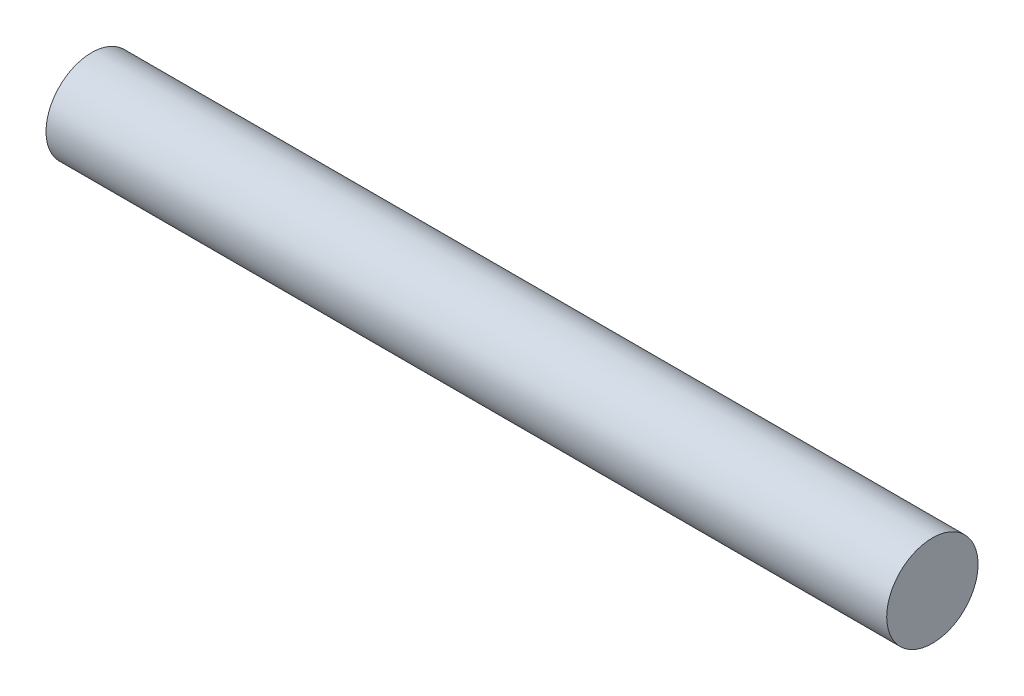
SolidWorks part; units mm, degrees
material "镀铬光轴"
ref_plane "前视" through (0, 0, 0) normal (0, 0, 1) x (1, 0, 0)
ref_plane "上视" through (0, 0, 0) normal (0, 1, 0) x (1, 0, 0)
ref_plane "右视" through (0, 0, 0) normal (1, 0, 0) x (0, 0, -1)
sketch "草图1" plane through (0, 0, 0) normal (0, 1, 0) x (1, 0, 0)
  line L0 (-1000, 0) -> (49000, 0) construction
  line L1 (0, 0) -> (0, 10)
  line L4 (0, 10) -> (184, 10)
  line L7 (184, 10) -> (184, 0)
  line L8 (184, 0) -> (0, 0)
  dimension "D1" = 20
  dimension "D4" = 184
revolve "旋转1" add sketch "草图1" angle 360 about L0
